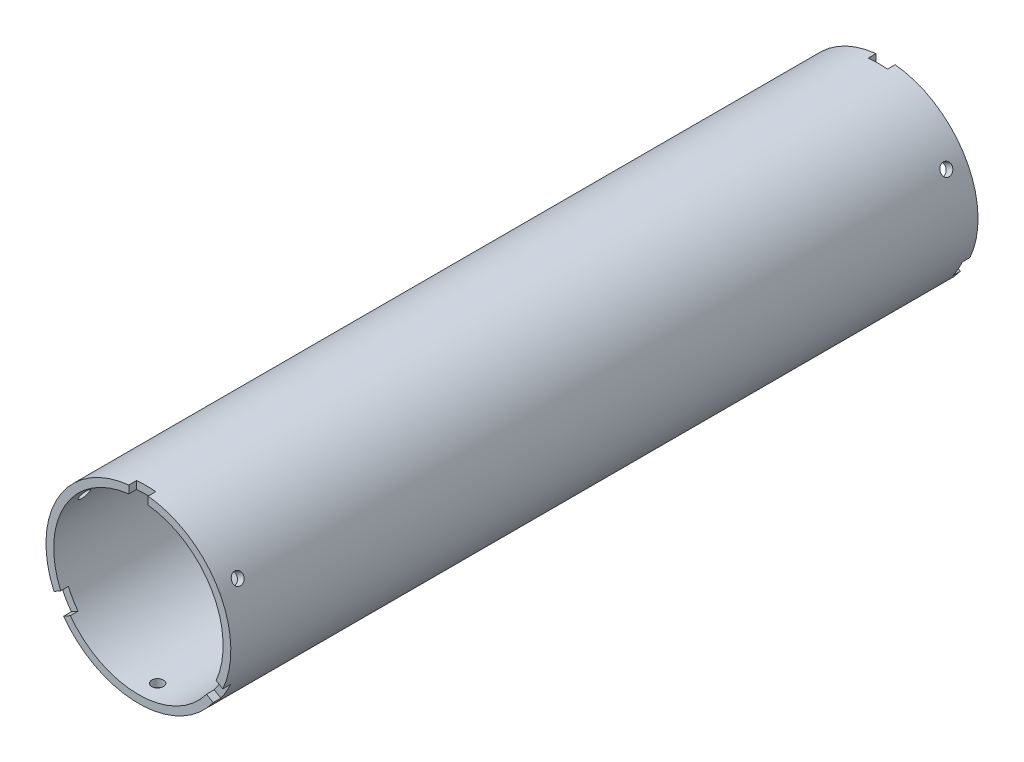
SolidWorks part; units mm, degrees
material "1060 Сплав"
ref_plane "Спереди" through (0, 0, 0) normal (0, 0, 1) x (1, 0, 0)
ref_plane "Сверху" through (0, 0, 0) normal (0, 1, 0) x (1, 0, 0)
ref_plane "Справа" through (0, 0, 0) normal (1, 0, 0) x (0, 0, -1)
sketch "Эскиз1" plane through (0, 0, 0) normal (0, 0, 1) x (1, 0, 0)
  circle A0 centre (0, 0) radius 24
  circle A1 centre (0, 0) radius 22
  dimension "D1" = 48
  dimension "D2" = 2
extrude "Бобышка-Вытянуть1" add sketch "Эскиз1" along normal blind 194
sketch "Эскиз2" plane through (0, 0, 0) normal (0, 1, 0) x (1, 0, 0)
  line L0 (0, 0) -> (0, -194) construction
  line L1 (22, 0) -> (-22, 0) construction
  line L2 (-24, -194) -> (24, -194) construction
  line L3 (24, 0) -> (-24, 0) construction
  circle A0 centre (0, -5) radius 1.5
  circle A1 centre (0, -189) radius 1.5
  dimension "D1" = 3
  dimension "D4" = 3
  dimension "D2" = 5
  dimension "D3" = 5
extrude "Вырез-Вытянуть1" cut sketch "Эскиз2" against normal blind 88
pattern_circular "Круговой массив1" count 3 over 360 about axis through (0, 0, 194) along (0, 0, -1) of "Вырез-Вытянуть1"
sketch "Эскиз3" plane through (0, 0, 0) normal (0, 0, -1) x (-1, 0, 0)
  line L0 (0, 0) -> (0, 38.5898) construction
  line L2 (-2.5, 28.6079) -> (2.5, 28.6079)
  line L3 (-2.5, 28.6079) -> (-2.5, 17.134)
  line L4 (-2.5, 17.134) -> (2.5, 17.134)
  line L5 (2.5, 28.6079) -> (2.5, 17.134)
  line L6 (-2.5, 28.6079) -> (2.5, 17.134) construction
  line L7 (-2.5, 17.134) -> (2.5, 28.6079) construction
  point P4 (0, 22.8709)
  dimension "D1" = 5
extrude "Вырез-Вытянуть2" cut sketch "Эскиз3" against normal blind 2
pattern_circular "Круговой массив2" count 3 over 360 about axis through (0, 0, 0) along (0, 0, 1) of "Вырез-Вытянуть2"
sketch "Эскиз4" plane through (0, 0, 194) normal (0, 0, 1) x (1, 0, 0)
  line L4 (2.5, 28.6079) -> (-2.5, 28.6079)
  line L5 (-2.5, 28.6079) -> (-2.5, 17.134)
  line L6 (-2.5, 17.134) -> (2.5, 17.134)
  line L7 (2.5, 17.134) -> (2.5, 28.6079)
  line L8 (2.5, 28.6079) -> (-2.5, 28.6079)
  line L9 (-2.5, 28.6079) -> (-2.5, 17.134)
  line L10 (-2.5, 17.134) -> (2.5, 17.134)
  line L11 (2.5, 17.134) -> (2.5, 28.6079)
  dimension "D1" = 0
extrude "Вырез-Вытянуть3" cut sketch "Эскиз4" against normal blind 2
pattern_circular "Круговой массив3" count 3 over 360 about axis through (0, 0, 0) along (0, 0, 1) of "Вырез-Вытянуть3"
